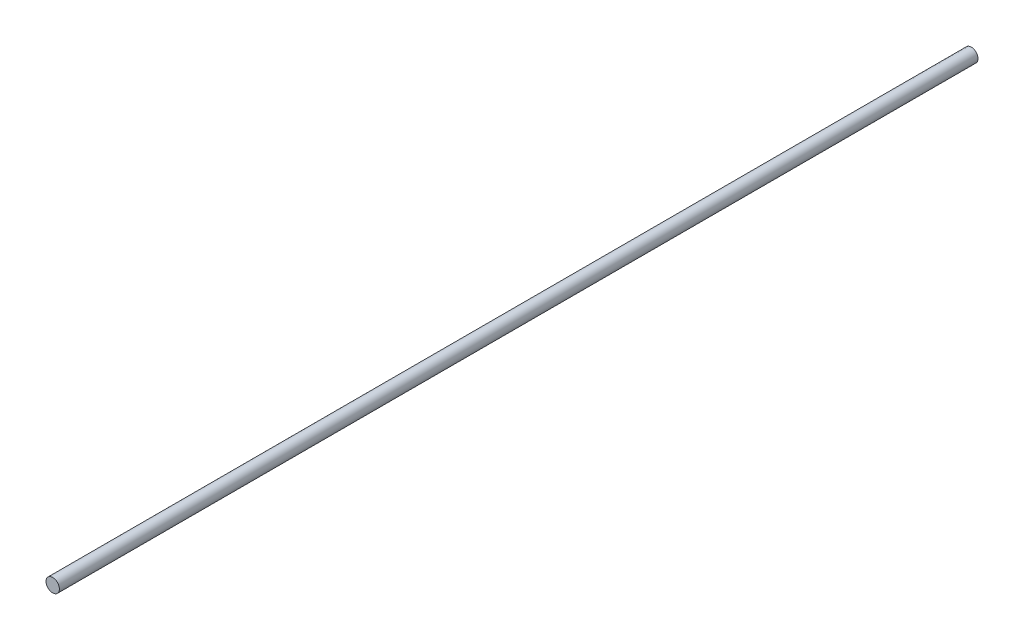
SolidWorks part; units mm, degrees
ref_plane "Front Plane" through (0, 0, 0) normal (0, 0, 1) x (1, 0, 0)
ref_plane "Top Plane" through (0, 0, 0) normal (0, 1, 0) x (1, 0, 0)
ref_plane "Right Plane" through (0, 0, 0) normal (1, 0, 0) x (0, 0, -1)
sketch "Sketch1" plane through (0, 0, 0) normal (0, 0, 1) x (1, 0, 0)
  circle A0 centre (2.0244, -11.4289) radius 1.5
  dimension "D1" = 3
extrude "Boss-Extrude1" add sketch "Sketch1" along normal blind 206
